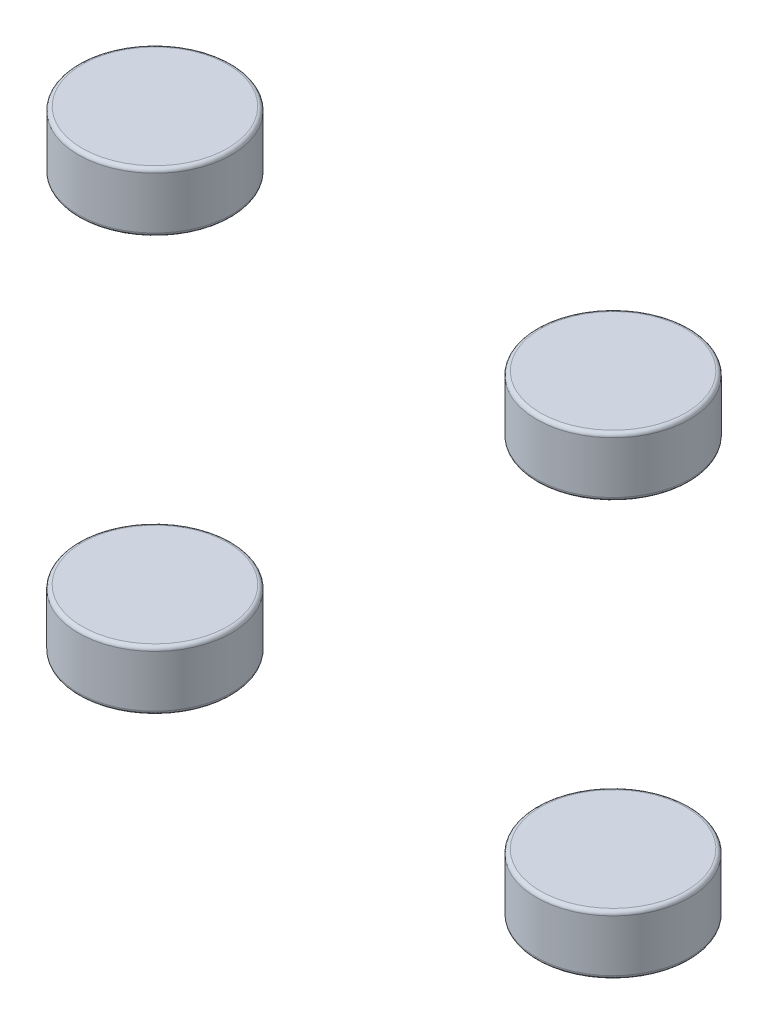
SolidWorks part; units mm, degrees
ref_plane "Front Plane" through (0, 0, 0) normal (0, 0, 1) x (1, 0, 0)
ref_plane "Top Plane" through (0, 0, 0) normal (0, 1, 0) x (1, 0, 0)
ref_plane "Right Plane" through (0, 0, 0) normal (1, 0, 0) x (0, 0, -1)
sketch3d "Left Suspension"
  line L0 (1180, -220, 108.03) -> (1122, -574, 138)
  line L1 (1122, -574, 138) -> (1020, -220, 136.03)
  line L2 (1020, -220, 136.03) -> (1180, -220, 108.03)
  line L3 (1030, -233, 255) -> (1170, -233, 242)
  line L4 (1170, -233, 242) -> (1150, -567.5, 313)
  line L5 (1150, -567.5, 313) -> (1030, -233, 255)
  line L6 (1165, -550.5, 318) -> (1165, -245, 393)
  line L7 (1165, -245, 393) -> (1165, -215, 393)
  line L8 (1165, -215, 393) -> (1165, -75, 333)
  line L9 (1165, -245, 393) -> (1155, -230, 333)
  line L10 (1155, -230, 333) -> (1175, -230, 333)
  line L11 (1175, -230, 333) -> (1165, -245, 393)
  line L12 (1165, -215, 393) -> (1155, -230, 333)
  line L13 (1165, -215, 393) -> (1175, -230, 333)
  line L14 (1244, -554, 222) -> (1251, -246, 222)
  line L15 (1130, -535, 233) -> (1244, -554, 222)
  line L16 (1130, -600, 235) -> (1130, -535, 233)
  line L34 (-420, -600, 235) -> (-420, -543.5, 233)
  line L35 (-420, -543.5, 233) -> (-412.5, -542, 156)
  line L36 (-490, -587, 155) -> (-491, -160, 151)
  line L37 (-412.5, -352, 446) -> (-446, -255, 425)
  line L38 (-380, -255, 425) -> (-412.5, -383, 405)
  line L39 (-446, -255, 425) -> (-412.5, -383, 405)
  line L40 (-380, -255, 425) -> (-446, -255, 425)
  line L41 (-412.5, -352, 446) -> (-380, -255, 425)
  line L42 (-412.5, -352, 446) -> (-412.5, -210.5, 587.5)
  line L43 (-412.5, -383, 405) -> (-412.5, -352, 446)
  line L44 (-412.5, -542, 156) -> (-412.5, -383, 405)
  line L45 (-578, -235, 280) -> (-416, -556, 332)
  line L46 (-270, -235, 280) -> (-578, -235, 280)
  line L47 (-416, -556, 332) -> (-270, -235, 280)
  line L48 (-427.5, -581, 127) -> (-236, -150, 142)
  line L49 (-536.5, -150, 117) -> (-427.5, -581, 127)
  line L50 (-236, -150, 142) -> (-536.5, -150, 117)
  point P1 (1180, -220, 108.03)
  point P2 (1122, -574, 138)
  point P11 (1170, -233, 242)
sketch3d "3D Sketch 1"
  circle A0 centre (-420, -600, 235) radius 259
  circle A1 centre (1130, -600, 235) radius 259
  point P2 (-420, -341, 235)
  point P6 (1130, -341, 235)
  point P9 (1130, -600, 235)
  dimension "D1" = 518
  dimension "D2" = 518
extrude "Left Wheels" add sketch "3D Sketch 1" along direction (0, 1, 0) on the side of the normal blind 201
fillet "Fillet1" radius 13 2 edges at (1130, -801, 494) (1130, -600, 494)
fillet "Fillet2" radius 13 2 edges at (-420, -801, 494) (-420, -600, 494)
sketch3d "Right sus"
  line L1 (1175, -230, 333) -> (1165, -245, 393) construction
  line L2 (1165, -215, 393) -> (1175, -230, 333) construction
  line L3 (1165, -245, 393) -> (1155, -230, 333) construction
  line L4 (1165, -215, 393) -> (1155, -230, 333) construction
  line L5 (1165, -215, 393) -> (1165, -75, 333) construction
  line L7 (1165, -550.5, 318) -> (1165, -245, 393) construction
  line L8 (1244, -554, 222) -> (1251, -246, 222) construction
  line L10 (1130, -600, 235) -> (1130, -535, 233) construction
  line L12 (-446, -255, 425) -> (-412.5, -383, 405) construction
  line L13 (-380, -255, 425) -> (-446, -255, 425) construction
  line L14 (-412.5, -352, 446) -> (-380, -255, 425) construction
  line L15 (-412.5, -352, 446) -> (-412.5, -210.5, 587.5) construction
  line L17 (-490, -587, 155) -> (-491, -160, 151) construction
  line L18 (-420, -600, 235) -> (-420, -543.5, 233) construction
  line L20 (-412.5, -542, 156) -> (-412.5, -383, 405) construction
  line L21 (-380, -255, 425) -> (-412.5, -383, 405) construction
  line L23 (1170, -233, 242) -> (1150, -567.5, 313) construction
  line L24 (1150, -567.5, 313) -> (1030, -233, 255) construction
  line L26 (1122, -574, 138) -> (1020, -220, 136.03) construction
  line L27 (1020, -220, 136.03) -> (1180, -220, 108.03) construction
  line L29 (-236, -150, 142) -> (-536.5, -150, 117) construction
  line L30 (-536.5, -150, 117) -> (-427.5, -581, 127) construction
  line L32 (-416, -556, 332) -> (-270, -235, 280) construction
  line L33 (-270, -235, 280) -> (-578, -235, 280) construction
  line L68 (-270, 235, 280) -> (-578, 235, 280)
  line L69 (-416, 556, 332) -> (-270, 235, 280)
  line L70 (-578, 235, 280) -> (-416, 556, 332)
  line L71 (-536.5, 150, 117) -> (-427.5, 581, 127)
  line L72 (-236, 150, 142) -> (-536.5, 150, 117)
  line L73 (-427.5, 581, 127) -> (-236, 150, 142)
  line L74 (1020, 220, 136.03) -> (1180, 220, 108.03)
  line L75 (1122, 574, 138) -> (1020, 220, 136.03)
  line L76 (1180, 220, 108.03) -> (1122, 574, 138)
  line L77 (1150, 567.5, 313) -> (1030, 233, 255)
  line L78 (1170, 233, 242) -> (1150, 567.5, 313)
  line L79 (1030, 233, 255) -> (1170, 233, 242)
  line L80 (-380, 255, 425) -> (-412.5, 383, 405)
  line L81 (-412.5, 542, 156) -> (-412.5, 383, 405)
  line L82 (-420, 543.5, 233) -> (-412.5, 542, 156)
  line L83 (-420, 600, 235) -> (-420, 543.5, 233)
  line L84 (-490, 587, 155) -> (-491, 160, 151)
  line L85 (-412.5, 383, 405) -> (-412.5, 352, 446)
  line L86 (-412.5, 352, 446) -> (-412.5, 210.5, 587.5)
  line L87 (-412.5, 352, 446) -> (-380, 255, 425)
  line L88 (-380, 255, 425) -> (-446, 255, 425)
  line L89 (-446, 255, 425) -> (-412.5, 383, 405)
  line L90 (-412.5, 352, 446) -> (-446, 255, 425)
  line L91 (1130, 600, 235) -> (1130, 535, 233)
  line L92 (1130, 535, 233) -> (1244, 554, 222)
  line L93 (1244, 554, 222) -> (1251, 246, 222)
  line L94 (1165, 550.5, 318) -> (1165, 245, 393)
  line L95 (1165, 245, 393) -> (1165, 215, 393)
  line L96 (1165, 215, 393) -> (1165, 75, 333)
  line L97 (1165, 215, 393) -> (1155, 230, 333)
  line L98 (1165, 245, 393) -> (1155, 230, 333)
  line L99 (1165, 215, 393) -> (1175, 230, 333)
  line L100 (1175, 230, 333) -> (1165, 245, 393)
  line L101 (1155, 230, 333) -> (1175, 230, 333)
sketch3d "3DSketch3"
  circle A0 centre (1130, 600, 235) radius 259
  circle A1 centre (-420, 600, 235) radius 259
  point P2 (1130, 859, 235)
  point P6 (-420, 859, 235)
  dimension "D1" = 518
  dimension "D2" = 518
extrude "Right Wheels" add sketch "3DSketch3" along direction (0, 1, 0) on the side of the normal blind 201 separate body
fillet "Fillet4" radius 13 2 edges at (-420, 600, 494) (-420, 801, 494)
fillet "Fillet3" radius 13 2 edges at (1130, 600, 494) (1130, 801, 494)
ref_plane "Plane1" through (-936, 0, 0) normal (1, 0, 0) x (0, 0, -1)
ref_plane "Ground" through (0, 0, -24) normal (0, 0, -1) x (-1, 0, 0)
